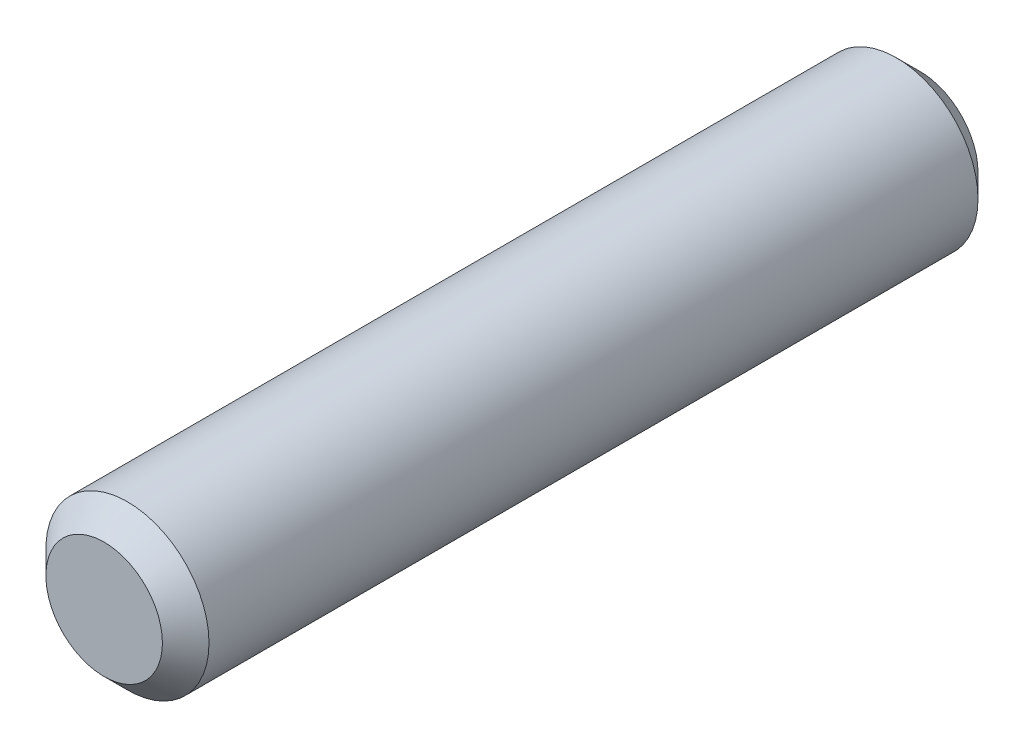
SolidWorks part; units mm, degrees
ref_plane "Front Plane" through (0, 0, 0) normal (0, 0, 1) x (1, 0, 0)
ref_plane "Top Plane" through (0, 0, 0) normal (0, 1, 0) x (1, 0, 0)
ref_plane "Right Plane" through (0, 0, 0) normal (1, 0, 0) x (0, 0, -1)
sketch "Sketch1" plane through (0, 0, 0) normal (0, 0, 1) x (1, 0, 0)
  circle A0 centre (0, 0) radius 7
  dimension "D1" = 14
extrude "Boss-Extrude1" add sketch "Sketch1" along normal blind 70
chamfer "Chamfer1" distance 2 angle 45 1 edges at (7, 0, 70)
chamfer "Chamfer2" distance 2 angle 45 1 edges at (7, 0, 0)
